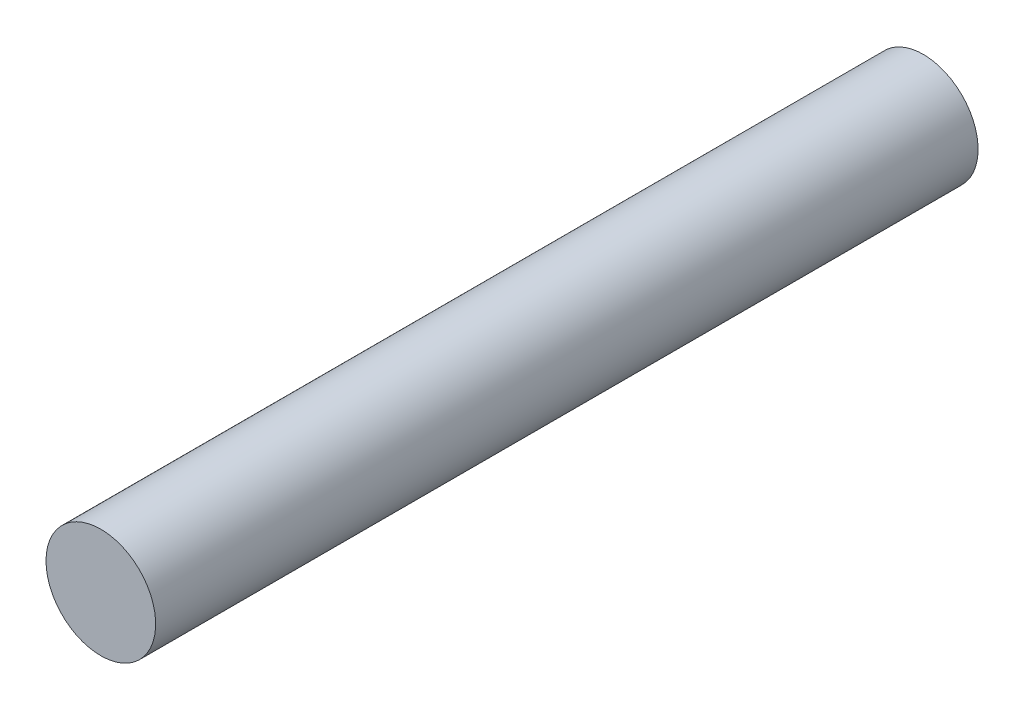
SolidWorks part; units mm, degrees
ref_plane "Спереди" through (0, 0, 0) normal (0, 0, 1) x (1, 0, 0)
ref_plane "Сверху" through (0, 0, 0) normal (0, 1, 0) x (1, 0, 0)
ref_plane "Справа" through (0, 0, 0) normal (1, 0, 0) x (0, 0, -1)
sketch "Эскиз1" plane through (0, 0, 0) normal (0, 0, 1) x (1, 0, 0)
  circle A0 centre (0, 0) radius 3
extrude "Вытянуть1" add sketch "Эскиз1" along normal blind 45
